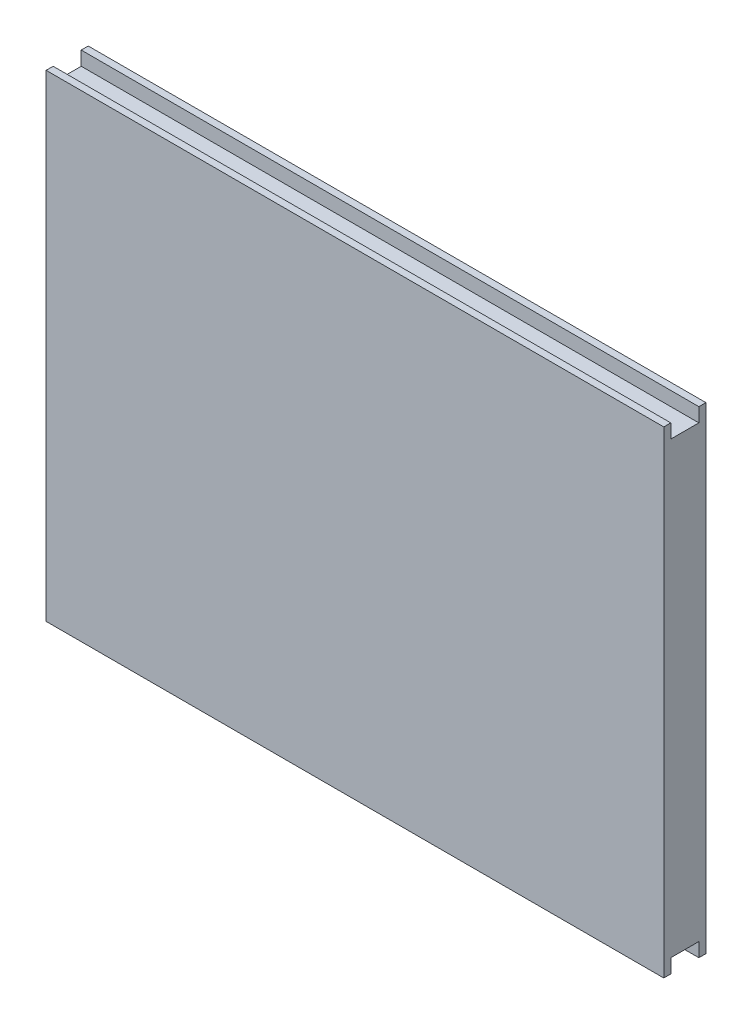
SolidWorks part; units mm, degrees
ref_plane "前视基准面" through (0, 0, 0) normal (0, 0, 1) x (1, 0, 0)
ref_plane "上视基准面" through (0, 0, 0) normal (0, 1, 0) x (1, 0, 0)
ref_plane "右视基准面" through (0, 0, 0) normal (1, 0, 0) x (0, 0, -1)
sketch "草图1" plane through (0, 0, 0) normal (1, 0, 0) x (0, 0, -1)
  line L4 (-5, 85) -> (-5, 80)
  line L5 (-5, 80) -> (5, 80)
  line L6 (5, 80) -> (5, 85)
  line L7 (-5, 85) -> (-7.5, 85)
  line L8 (5, 85) -> (7.5, 85)
  line L9 (0, 0) -> (34.3064, 0) construction
  line L10 (5, -85) -> (7.5, -85)
  line L11 (5, -80) -> (5, -85)
  line L12 (-5, -80) -> (5, -80)
  line L13 (-5, -85) -> (-5, -80)
  line L14 (-5, -85) -> (-7.5, -85)
  line L15 (-7.5, 85) -> (-7.5, -85)
  line L16 (7.5, 85) -> (7.5, -85)
extrude "凸台-拉伸1" add sketch "草图1" along normal blind 220
